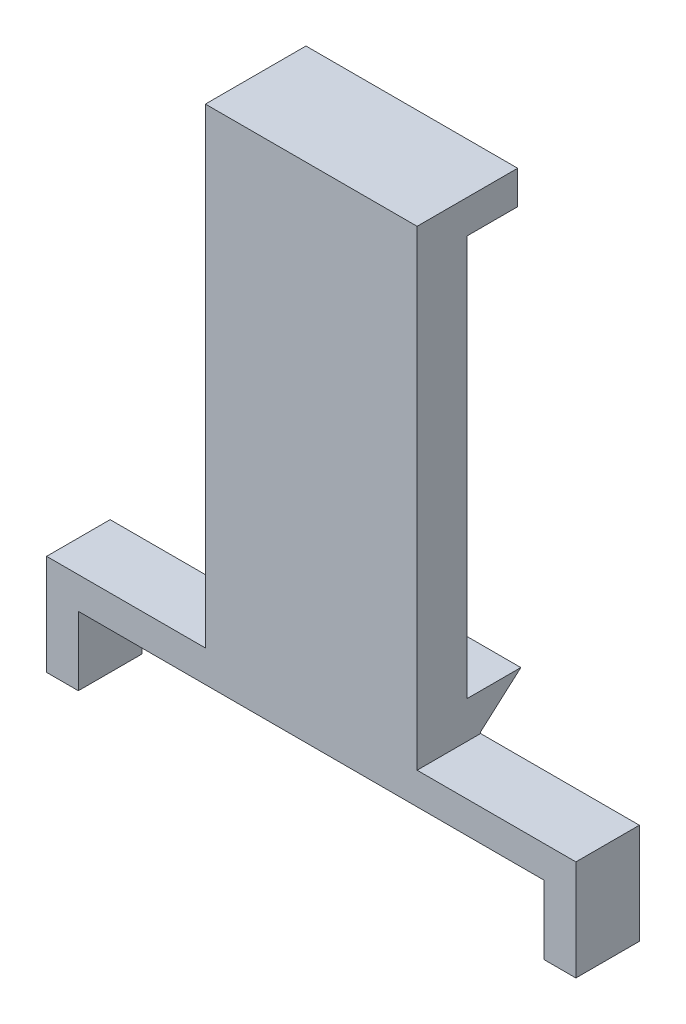
SolidWorks part; units mm, degrees
ref_plane "Front Plane" through (0, 0, 0) normal (0, 0, 1) x (1, 0, 0)
ref_plane "Top Plane" through (0, 0, 0) normal (0, 1, 0) x (1, 0, 0)
ref_plane "Right Plane" through (0, 0, 0) normal (1, 0, 0) x (0, 0, -1)
sketch "Sketch1" plane through (0, 0, 0) normal (1, 0, 0) x (0, 0, -1)
  line L0 (-9.8, -6.5) -> (-3.8, -6.5)
  line L1 (-3.8, -6.5) -> (-3.8, -3.3571)
  line L2 (-3.8, -3.3571) -> (0, 0)
  line L3 (0, 0) -> (-5.1, 0)
  line L4 (-5.1, 0) -> (-5.1, 37.85)
  line L5 (-5.1, 37.85) -> (-0.3, 37.85)
  line L6 (-0.3, 37.85) -> (-0.3, 41)
  line L7 (-0.3, 41) -> (-9.8, 41)
  line L8 (-9.8, 41) -> (-9.8, -6.5)
  dimension "D1" = 6
  dimension "D2" = 9.5
  dimension "D3" = 37.85
  dimension "D4" = 41
  dimension "D5" = 4.7
  dimension "D6" = 9.8
  dimension "D7" = 6.5
  dimension "D8" = 3.6
extrude "Boss-Extrude1" add sketch "Sketch1" along normal blind 20 contours L8 L0 L1 L2 L3 L4 L5 L6 L7
sketch "Sketch2" plane through (0, -6.5, 0) normal (0, -1, 0) x (1, 0, 0)
  line L0 (20, 0) -> (0, 0) construction
  line L1 (-5, 9.8) -> (25, 9.8)
  line L2 (-5, 9.8) -> (-5, 3.8)
  line L3 (-5, 3.8) -> (25, 3.8)
  line L4 (25, 9.8) -> (25, 3.8)
  line L5 (20, 9.8) -> (0, 9.8) construction
  line L6 (20, 3.8) -> (0, 3.8) construction
  point P6 (10, 0)
  point P7 (10, 9.8)
  dimension "D1" = 30
extrude "Boss-Extrude2" add sketch "Sketch2" against normal blind 3 contours L2 L1 L4 L3
sketch "Sketch3" plane through (0, 0, 3.8) normal (0, 0, -1) x (-1, 0, 0)
  line L0 (-25, -6.5) -> (5, -6.5) construction
  line L1 (-35, -3.5) -> (15, -3.5)
  line L2 (-35, -3.5) -> (-35, -6.5)
  line L3 (-35, -6.5) -> (15, -6.5)
  line L4 (15, -3.5) -> (15, -6.5)
  line L5 (5, -3.5) -> (0, -3.5) construction
  line L6 (-20, -3.3571) -> (0, -3.3571) construction
  point P10 (-10, -3.3571)
  point P11 (-10, -3.5)
  dimension "D1" = 50
extrude "Boss-Extrude3" add sketch "Sketch3" against normal up to surface (6 mm away) up to face at (10, 6.875, 9.8)
sketch "Sketch4" plane through (0, -6.5, 0) normal (0, -1, 0) x (1, 0, 0)
  line L0 (35, 3.8) -> (-15, 3.8) construction
  line L1 (-15, 9.8) -> (-12, 9.8)
  line L2 (-15, 9.8) -> (-15, 3.8)
  line L3 (-15, 3.8) -> (-12, 3.8)
  line L4 (-12, 9.8) -> (-12, 3.8)
  line L5 (10, 0) -> (10, 18.2118) construction
  line L6 (20, 0) -> (0, 0) construction
  line L7 (35, 3.8) -> (32, 3.8)
  line L8 (32, 9.8) -> (32, 3.8)
  line L9 (35, 9.8) -> (32, 9.8)
  line L10 (35, 9.8) -> (35, 3.8)
  dimension "D1" = 3
extrude "Boss-Extrude4" add sketch "Sketch4" along normal blind 6.5 contours L2 L1 L4 L3 | L10 L7 L8 L9
